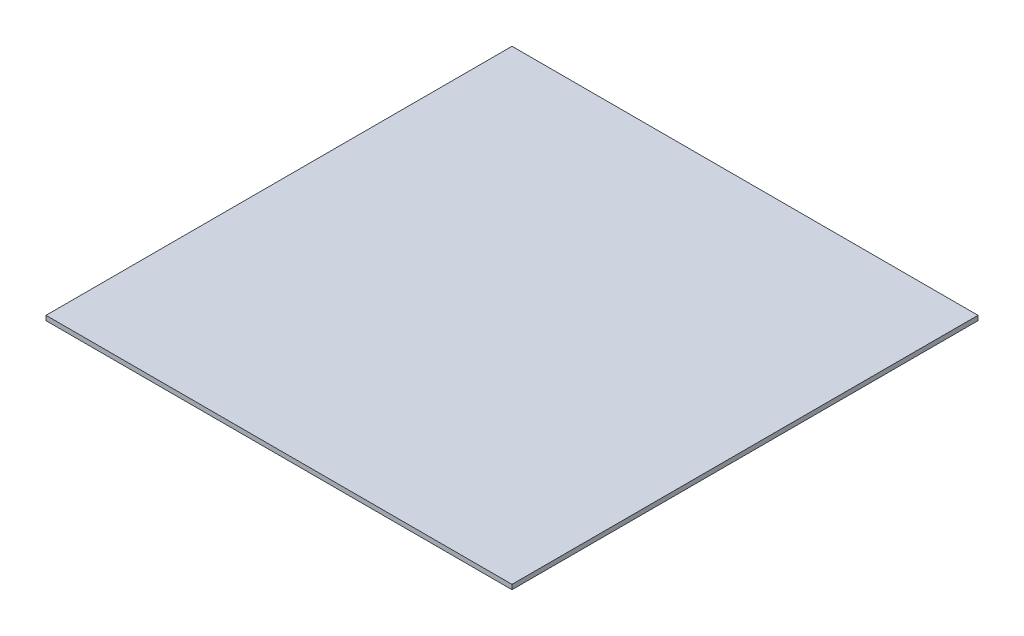
SolidWorks part; units mm, degrees
material "2.0060 (Cu-ETP)"
ref_plane "Front Plane" through (0, 0, 0) normal (0, 0, 1) x (1, 0, 0)
ref_plane "Top Plane" through (0, 0, 0) normal (0, 1, 0) x (1, 0, 0)
ref_plane "Right Plane" through (0, 0, 0) normal (1, 0, 0) x (0, 0, -1)
sketch "Sketch1" plane through (0, 0, 0) normal (0, 1, 0) x (1, 0, 0)
  line L1 (-50, -50) -> (50, -50)
  line L2 (-50, -50) -> (-50, 50)
  line L3 (-50, 50) -> (50, 50)
  line L4 (50, -50) -> (50, 50)
  line L5 (-50, -50) -> (50, 50) construction
  line L6 (-50, 50) -> (50, -50) construction
  point P0 (0, 0)
  dimension "D1" = 100
  dimension "D2" = 100
extrude "Boss-Extrude1" add sketch "Sketch1" along normal blind 1
